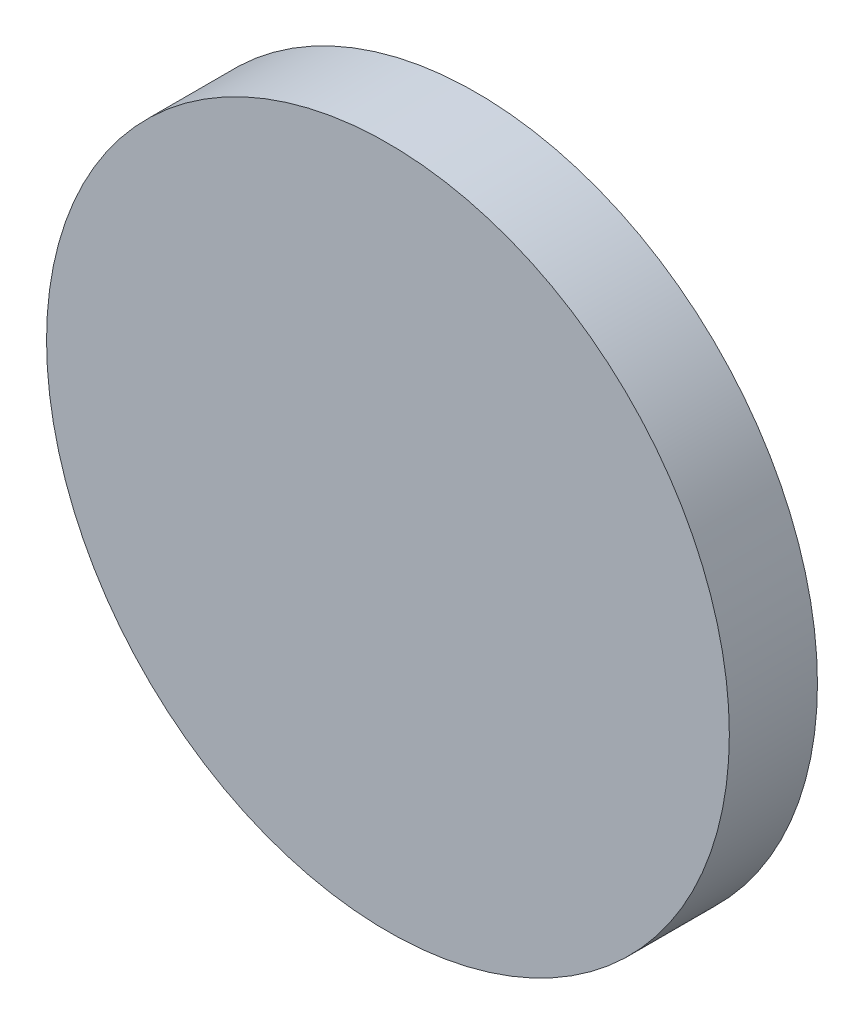
SolidWorks part; units mm, degrees
ref_plane "前视基准面" through (0, 0, 0) normal (0, 0, 1) x (1, 0, 0)
ref_plane "上视基准面" through (0, 0, 0) normal (0, 1, 0) x (1, 0, 0)
ref_plane "右视基准面" through (0, 0, 0) normal (1, 0, 0) x (0, 0, -1)
sketch "草图1" plane through (0, 0, 0) normal (0, 0, 1) x (1, 0, 0)
  circle A0 centre (0, 0) radius 38.75
  dimension "D1" = 77.5
extrude "凸台-拉伸1" add sketch "草图1" along normal blind 10
sketch "草图2" plane through (0, 0, 0) normal (0, 0, -1) x (-1, 0, 0)
  circle A0 centre (0, 0) radius 37
  dimension "D1" = 74
extrude "切除-拉伸1" cut sketch "草图2" against normal blind 7
